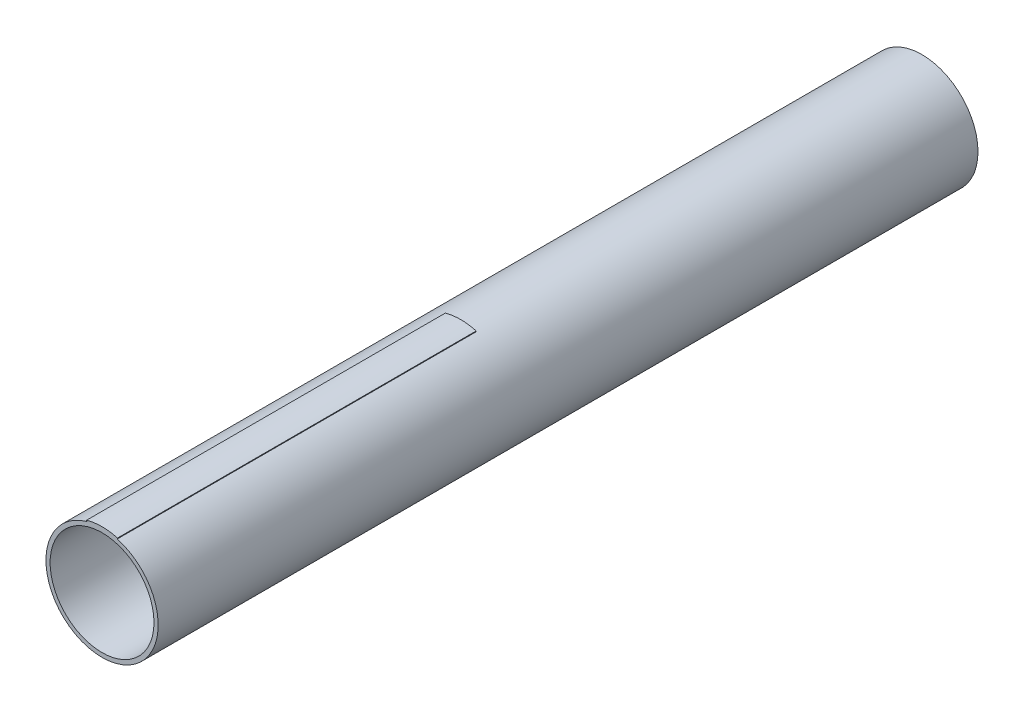
SolidWorks part; units mm, degrees
material "PVC Rigid"
ref_plane "Front Plane" through (0, 0, 0) normal (0, 0, 1) x (1, 0, 0)
ref_plane "Top Plane" through (0, 0, 0) normal (0, 1, 0) x (1, 0, 0)
ref_plane "Right Plane" through (0, 0, 0) normal (1, 0, 0) x (0, 0, -1)
sketch "Sketch1" plane through (0, 0, 0) normal (0, 0, 1) x (1, 0, 0)
  line L0 (101.3587, 0) -> (109.5375, 0) construction
  circle A0 centre (0, 0) radius 109.5375 construction
  circle A1 centre (0, 0) radius 101.3587 construction
  dimension "ID" = 202.7174
  dimension "OD" = 219.075
  dimension "Wall Thickness" = 8.1788
sketch "Sketch2" plane through (0, 0, 0) normal (1, 0, 0) x (0, 0, -1)
  line L0 (-800, 0) -> (800, 0) construction
  line L1 (-526.1562, 109.5375) -> (-526.1562, -109.5375) construction
  line L2 (526.1563, 109.5375) -> (526.1563, -109.5375) construction
  point P4 (0, 0)
  point P8 (-526.1562, 0)
  point P11 (526.1563, 0)
  dimension "Length" = 1600
  dimension "D1" = 273.8438
  dimension "D2" = 273.8438
  dimension "D3" = 219.075
sketch "Sketch3" plane through (0, 0, 0) normal (0, 0, 1) x (1, 0, 0)
  circle A0 centre (0, 0) radius 109.5375
  circle A1 centre (0, 0) radius 109.5375 construction
  circle A2 centre (0, 0) radius 101.3587 construction
  circle A3 centre (0, 0) radius 101.3587
extrude "Boss-Extrude1" add sketch "Sketch3" along normal up to vertex (800 mm away) and the other way up to vertex (800 mm away) up to point (0, 0, 800) other way up to point (0, 0, -800)
ref_plane "Plane1" through (0, 0, 750) normal (0, 0, 1) x (1, 0, 0)
ref_plane "Plane2" through (0, 0, 100) normal (0, 0, -1) x (-1, 0, 0)
ref_plane "Plane3" through (0, 109.5375, 0) normal (0, 1, 0) x (1, 0, 0)
sketch "Sketch9" plane through (0, 109.5375, 0) normal (0, 1, 0) x (1, 0, 0)
  line L0 (-30, -100) -> (-30, -800)
  line L1 (30, -100) -> (30, -800)
  line L3 (120.4912, -100) -> (-120.4912, -100) construction
  line L4 (-109.5375, -800) -> (109.5375, -800) construction
  line L5 (0, -120.4912) -> (0, 120.4912) construction
  line L6 (-30, -100) -> (30, -100)
  line L7 (-30, -800) -> (30, -800)
  dimension "D1" = 60
  dimension "D2" = 30
wrap "Wrap2" sketch "Sketch9" wrap type emboss source sketch "Sketch9" thickness 2 face at (109.5375, 0, 800) parameters "D1"=2
equation "\"D1@Sketch2\"=\"OD@Sketch1\" * 1.25"
equation "\"D2@Sketch2\"=\"D1@Sketch2\""
equation "\"D3@Sketch2\"= \"OD@Sketch1\""
